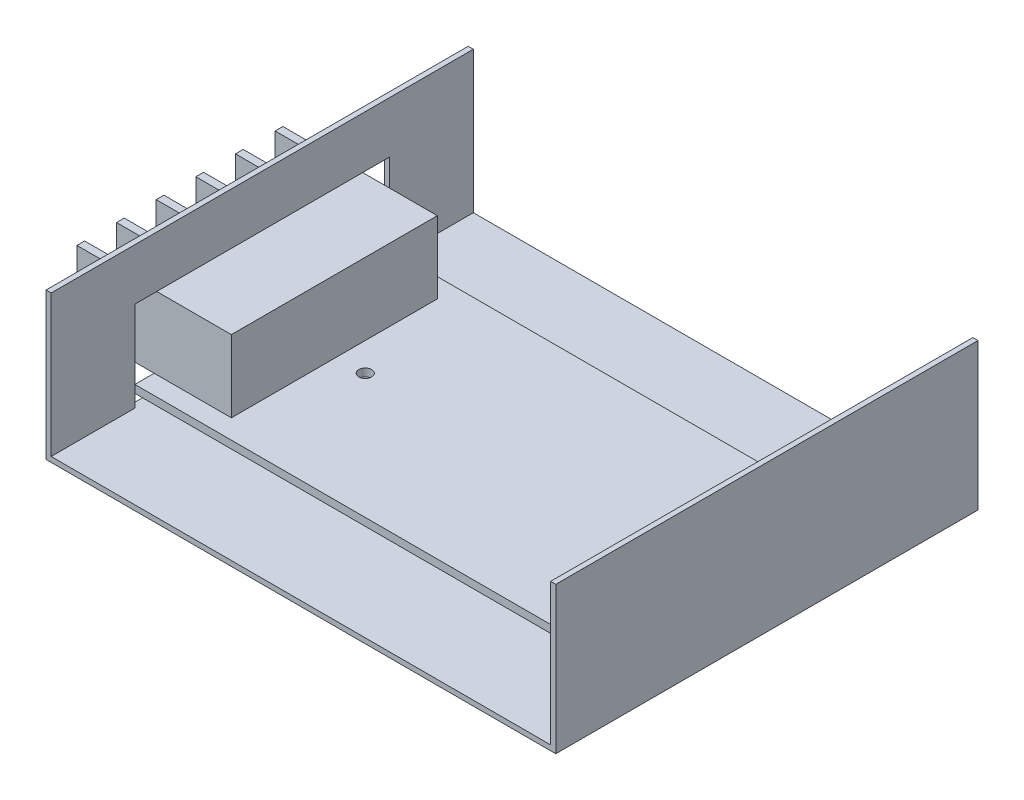
SolidWorks part; units mm, degrees
ref_plane "Спереди" through (0, 0, 0) normal (0, 0, 1) x (1, 0, 0)
ref_plane "Сверху" through (0, 0, 0) normal (0, 1, 0) x (1, 0, 0)
ref_plane "Справа" through (0, 0, 0) normal (1, 0, 0) x (0, 0, -1)
sketch "Эскиз1" plane through (0, 0, 0) normal (0, 0, 1) x (1, 0, 0)
  line L0 (1, 1) -> (98, 1)
  line L1 (98, 1) -> (98, 28.5)
  line L2 (1, 28.5) -> (1, 1)
  line L3 (0, 0) -> (99, 0)
  line L4 (99, 0) -> (99, 28.5)
  line L5 (99, 28.5) -> (98, 28.5)
  line L6 (0, 28.5) -> (0, 0)
  line L7 (1, 28.5) -> (0, 28.5)
  point P8 (98.5, 28.5)
  dimension "D1" = 1
  dimension "D2" = 1
  dimension "D3" = 1
  dimension "D4" = 28.5
  dimension "D5" = 99
extrude "Бобышка-Вытянуть1" add sketch "Эскиз1" along normal blind 82
sketch "Эскиз2" plane through (0, 0, 0) normal (-1, 0, 0) x (0, 0, 1)
  line L0 (16.25, 18.5) -> (65.75, 18.5)
  line L6 (82, 28.5) -> (82, 0) construction
  line L7 (65.75, 18.5) -> (65.75, 1)
  line L8 (16.25, 1) -> (65.75, 1)
  line L9 (16.25, 1) -> (16.25, 18.5)
  line L10 (82, 0) -> (0, 0) construction
  dimension "D1" = 17.5
  dimension "D2" = 49.5
  dimension "D3" = 16.25
  dimension "D4" = 1
extrude "Вырез-Вытянуть1" cut sketch "Эскиз2" against normal blind 10
sketch "Эскиз3" plane through (98, 0, 0) normal (-1, 0, 0) x (0, 0, 1)
  line L0 (65.75, 1) -> (65.75, 18.5) construction
  line L6 (17.25, 2.5) -> (64.75, 2.5)
  line L7 (64.75, 2.5) -> (64.75, 4)
  line L8 (64.75, 4) -> (17.25, 4)
  line L9 (17.25, 4) -> (17.25, 2.5)
  dimension "D1" = 1.5
  dimension "D2" = 47.5
  dimension "D3" = 1
extrude "Бобышка-Вытянуть2" add sketch "Эскиз3" along normal up to surface (98 mm away) up to face at (0, 9.75, 41)
sketch "Эскиз4" plane through (0, 4, 0) normal (0, 1, 0) x (1, 0, 0)
  line L0 (-15, -21) -> (15, -21)
  line L2 (15, -21) -> (15, -61)
  line L3 (15, -61) -> (-15, -61)
  line L4 (-15, -61) -> (-15, -21)
  line L5 (1, -82) -> (1, 0) construction
  line L6 (0, -17.25) -> (98, -17.25) construction
  dimension "D1" = 30
  dimension "D2" = 40
  dimension "D3" = 14
  dimension "D4" = 3.75
extrude "Бобышка-Вытянуть3" add sketch "Эскиз4" along normal blind 14
sketch "Эскиз5" plane through (0, 18, 0) normal (0, 1, 0) x (1, 0, 0)
  line L0 (-7, -22.5) -> (-15, -22.5)
  line L1 (-7, -53.3) -> (-7, -59.5)
  line L2 (-7, -28.7) -> (-15, -28.7)
  line L3 (-15, -30.2) -> (-7, -30.2)
  line L4 (-15, -53.3) -> (-15, -59.5)
  line L5 (-15, -36.4) -> (-7, -36.4)
  line L6 (-7, -37.9) -> (-15, -37.9)
  line L7 (-15, -45.6) -> (-15, -51.8)
  line L8 (-15, -44.1) -> (-7, -44.1)
  line L9 (-7, -45.6) -> (-15, -45.6)
  line L10 (-7, -45.6) -> (-7, -51.8)
  line L11 (-7, -51.8) -> (-15, -51.8)
  line L12 (-15, -53.3) -> (-7, -53.3)
  line L13 (-15, -37.9) -> (-15, -44.1)
  line L14 (-15, -59.5) -> (-7, -59.5)
  line L15 (-7, -37.9) -> (-7, -44.1)
  line L16 (-15, -30.2) -> (-15, -36.4)
  line L17 (-7, -30.2) -> (-7, -36.4)
  line L18 (-15, -22.5) -> (-15, -28.7)
  line L19 (-7, -22.5) -> (-7, -28.7)
extrude "Вырез-Вытянуть2" cut sketch "Эскиз5" against normal blind 24
chamfer "Фаска1" distance 2 angle 45 10 edges at (-7, 4, 25.6) (-7, 4, 33.3) (-7, 4, 41) (-7, 4, 48.7) (-7, 4, 56.4) (-7, 18, 56.4) (-7, 18, 48.7) (-7, 18, 41) (-7, 18, 33.3) (-7, 18, 25.6)
hole_wizard "Отверстие обработанное метчиком M31" positions "Эскиз6" profile "Эскиз7" tap size "M3" standard "ISO"
sketch "Эскиз6" plane through (0, 0, 0) normal (0, -1, 0) x (-1, 0, 0)
  line L3 (0, 0) -> (-99, 0) construction
  line L4 (0, -82) -> (0, 0) construction
  point P0 (-20.5, -40.5)
  point P2 (-75.5, -40.5)
  dimension "D1" = 55
  dimension "D2" = 0
  dimension "D3" = 40.5
  dimension "D4" = 20.5
sketch "Эскиз7" plane through (20.5, 0, 40.5) normal (1, 0, 0) x (0, 0, -1)
  line L0 (0, 0) -> (0, 9.2511)
  line L1 (0, 9.2511) -> (1.25, 8.5)
  line L2 (1.25, 8.5) -> (1.25, 0)
  line L5 (1.25, 0) -> (0, 0)
  line L10 (0, 9.2511) -> (-1.25, 8.5) construction
  line L11 (0, -6.35) -> (0, 107.95) construction
  dimension "Диаметр сверла" = 2.5
  dimension "Глубина сверла" = 8.5
  dimension "Угол заточки сверла" = 118
cosmetic thread "Отверстие резьбы1" parameters "D1"=4, "D2"=3
cosmetic thread "Отверстие резьбы2" parameters "D1"=4, "D2"=3
